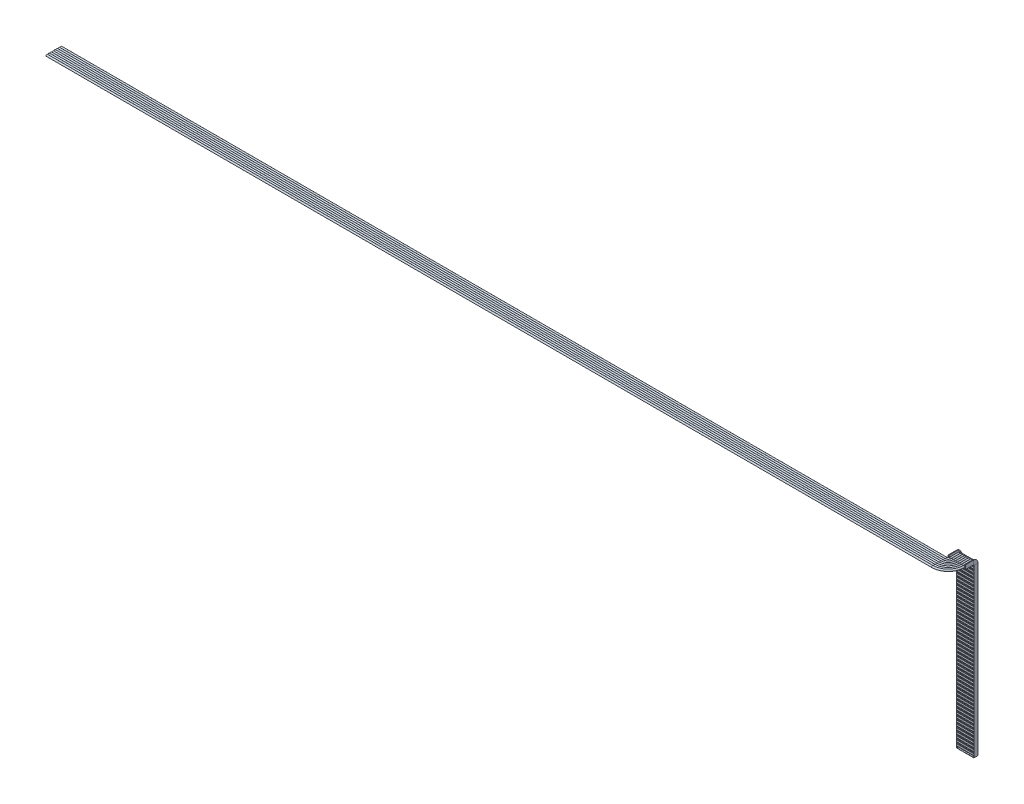
SolidWorks part; units mm, degrees
ref_plane "Alzado" through (0, 0, 0) normal (0, 0, 1) x (1, 0, 0)
ref_plane "Planta" through (0, 0, 0) normal (0, 1, 0) x (1, 0, 0)
ref_plane "Vista lateral" through (0, 0, 0) normal (1, 0, 0) x (0, 0, -1)
sketch "Croquis1" plane through (0, 0, 0) normal (0, 1, 0) x (1, 0, 0)
  line L1 (-300, 72.5) -> (300, 72.5)
  line L2 (-300, 72.5) -> (-300, -72.5)
  line L3 (-300, -72.5) -> (300, -72.5)
  line L4 (300, 72.5) -> (300, -72.5)
  line L5 (-300, 72.5) -> (300, -72.5) construction
  line L6 (-300, -72.5) -> (300, 72.5) construction
  point P0 (0, 0)
  dimension "D1" = 600
  dimension "D2" = 145
extrude "Saliente-Extruir1" add sketch "Croquis1" along normal blind 10
sketch "Croquis2" plane through (0, 10, 0) normal (0, 1, 0) x (1, 0, 0)
  line L0 (-300, 72.5) -> (-300, -72.5)
  line L1 (-300, -72.5) -> (300, -72.5)
  line L2 (300, -72.5) -> (300, 72.5)
  line L3 (300, 72.5) -> (280, 72.5)
  line L4 (300, 72.5) -> (-300, 72.5) construction
  line L5 (280, 72.5) -> (280, -47.5)
  line L6 (280, -47.5) -> (-280, -47.5)
  line L7 (-280, -47.5) -> (-280, 72.5)
  line L8 (-280, 72.5) -> (-300, 72.5)
  dimension "D1" = 20
  dimension "D2" = 20
  dimension "D3" = 25
sketch3d "Croquis3D1"
  line L0 (0, 0, 0) -> (0, 5826.5, 0)
  line L1 (0, 5916.5, 90) -> (0, 5916.5, 367.5)
  arc A0 (0, 5826.5, 0) -> (0, 5916.5, 90) centre (0, 5826.5, 90) ccw
  point P6 (0, 5916.5, 0)
  point P7 (90, 5826.5, 90)
  dimension "D3" = 90
  dimension "D1" = 5916.5
  dimension "D2" = 367.5
sweep "Barrer1" add profiles "Croquis2" path "Croquis3D1"
sketch "Croquis3" plane through (0, 0, 47.5) normal (0, 0, -1) x (-1, 0, 0)
  line L0 (-280, 10) -> (280, 10)
  line L1 (280, 10) -> (280, 69.0243)
  line L2 (280, 10) -> (280, 5826.5) construction
  line L3 (280, 69.0243) -> (-280, 69.0243)
  line L4 (-280, 10) -> (-280, 5826.5) construction
  line L5 (-280, 69.0243) -> (-280, 10)
extrude "Cortar-Extruir1" cut sketch "Croquis3" against normal blind 78
pattern_linear "MatrizL1" count 50 spacing 120 along (0, 1, 0) of "Cortar-Extruir1"
sketch "Croquis4" plane through (0, 5869, 0) normal (0, 1, 0) x (1, 0, 0)
  line L0 (280, -90) -> (-280, -90)
  line L1 (-280, -90) -> (-280, -121.6638)
  line L2 (-280, -90) -> (-280, -367.5) construction
  line L3 (-280, -121.6638) -> (280, -121.6638)
  line L4 (280, -90) -> (280, -367.5) construction
  line L5 (280, -121.6638) -> (280, -90)
extrude "Cortar-Extruir2" cut sketch "Croquis4" against normal blind 78
pattern_linear "MatrizL2" count 7 spacing 50 along (0, 0, 1) of "Cortar-Extruir2"
sketch "Croquis5" plane through (0, 10, 0) normal (0, 1, 0) x (1, 0, 0)
  line L0 (280, 0) -> (-280, 0) construction
  line L1 (280, 72.5) -> (280, -72.5) construction
  line L2 (-280, -72.5) -> (-280, 72.5) construction
  circle A0 centre (245.0133, 0) radius 30
  circle A1 centre (175.0133, 0) radius 30
  circle A2 centre (105.0133, 0) radius 30
  circle A3 centre (35.0133, 0) radius 30
  circle A4 centre (-34.9867, 0) radius 30
  circle A5 centre (-104.9867, 0) radius 30
  circle A6 centre (-174.9867, 0) radius 30
  circle A7 centre (-244.9867, 0) radius 30
  point P9 (127.4246, 0)
  point P23 (-211.6101, 0)
  point P24 (201.7195, 0)
  point P25 (-154.7887, 0)
  point P26 (233.7961, 0)
  point P27 (245.0133, 0)
  dimension "D1" = 60
  dimension "D3" = 70
  dimension "D2" = 8
sketch3d "Croquis3D2"
  line L0 (245.0133, 10, 0) -> (245.0133, 5856.9897, 0)
  line L1 (245.0133, 5906.9897, 50) -> (245.0133, 5906.9897, 244.5096)
  arc A0 (245.0133, 5856.9897, 0) -> (245.0133, 5906.9897, 50) centre (245.0133, 5856.9897, 50) ccw
  point P6 (245.0133, 5906.9897, 0)
  point P7 (295.0133, 5856.9897, 50)
  point P8 (245.0133, 5906.9897, 292.8214)
  point P9 (245.0133, 5906.9897, 244.5096)
  dimension "D1" = 50
  dimension "D2" = 5896.9897
sweep "Barrer2" add profiles "Croquis5" path "Croquis3D2"
sketch "Croquis6" plane through (0, 0, 244.5096) normal (0, 0, 1) x (1, 0, 0)
  circle A0 centre (245.0133, 5906.9897) radius 30
  circle A1 centre (175.0133, 5906.9897) radius 30
  circle A2 centre (105.0133, 5906.9897) radius 30
  circle A3 centre (35.0133, 5906.9897) radius 30
  circle A4 centre (-34.9867, 5906.9897) radius 30
  circle A5 centre (-104.9867, 5906.9897) radius 30
  circle A6 centre (-174.9867, 5906.9897) radius 30
  circle A7 centre (-244.9867, 5906.9897) radius 30
  dimension "D1" = 8
sketch3d "Croquis3D3"
  line L0 (245.0133, 5906.9897, 244.5096) -> (245.0133, 5906.9897, 363.5096)
  line L1 (-304.9867, 5906.9897, 913.5096) -> (-31235.2767, 5906.9897, 913.5096)
  arc A0 (245.0133, 5906.9897, 363.5096) -> (-304.9867, 5906.9897, 913.5096) centre (-304.9867, 5906.9897, 363.5096) ccw
  point P6 (245.0133, 5906.9897, 913.5096)
  point P7 (-304.9867, 5356.9897, 363.5096)
  dimension "D1" = 550
  dimension "D2" = 669
  dimension "D3" = 31480.29
sweep "Barrer10" add profiles "Croquis6" path "Croquis3D3"
